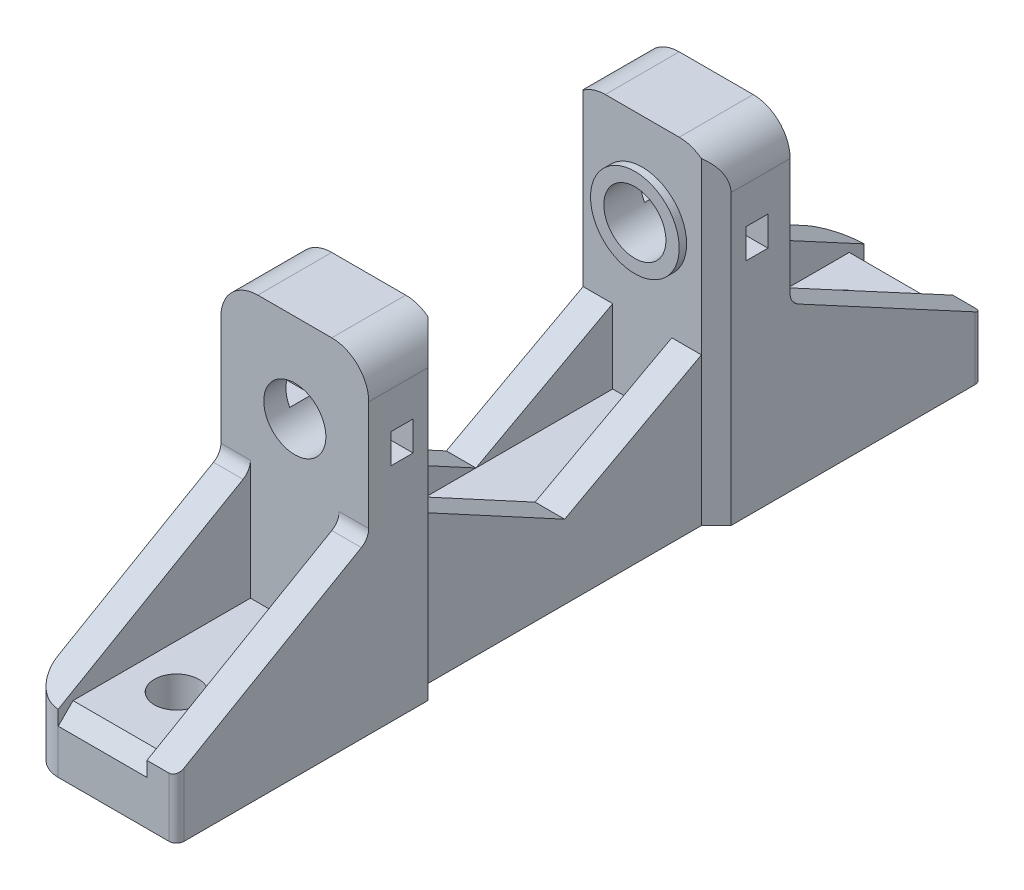
SolidWorks part; units mm, degrees
ref_plane "Спереди" through (0, 0, 0) normal (0, 0, 1) x (1, 0, 0)
ref_plane "Сверху" through (0, 0, 0) normal (0, 1, 0) x (1, 0, 0)
ref_plane "Справа" through (0, 0, 0) normal (1, 0, 0) x (0, 0, -1)
sketch "Эскиз1" plane through (0, 0, 0) normal (0, 0, 1) x (1, 0, 0)
  line L0 (-10, 0) -> (10, 0)
  line L2 (-10, 0) -> (-10, 44)
  line L3 (-10, 44) -> (10, 44)
  line L4 (10, 44) -> (10, 0)
  circle A0 centre (0, 32) radius 4.2
extrude "Бобышка-Вытянуть1" add sketch "Эскиз1" along normal blind 7
ref_plane "Плоскость1" through (0, 0, 7) normal (0, 0, 1) x (1, 0, 0)
sketch "Эскиз2" plane through (0, 0, 7) normal (0, 0, 1) x (1, 0, 0)
  line L0 (-10, 44) -> (10, 44)
  line L1 (10, 44) -> (10, 0)
  line L2 (10, 0) -> (-10, 0)
  line L3 (-10, 0) -> (-10, 44)
extrude "Бобышка-Вытянуть2" add sketch "Эскиз2" along normal blind 3
sketch "Эскиз3" plane through (0, 0, 0) normal (0, 1, 0) x (1, 0, 0)
  line L0 (-10, -10) -> (-10, -36)
  line L1 (-10, -36) -> (10, -36)
  line L2 (10, -36) -> (10, -10)
  line L3 (-10, -10) -> (10, -10)
  circle A0 centre (0, -26) radius 3
extrude "Бобышка-Вытянуть4" add sketch "Эскиз3" along normal blind 8
ref_plane "Плоскость2" through (-10, 0, 0) normal (-1, 0, 0) x (0, 0, 1)
sketch "Эскиз4" plane through (-10, 0, 0) normal (-1, 0, 0) x (0, 0, 1)
  line L0 (36, 8) -> (10, 8)
  line L1 (10, 8) -> (10, 23)
  line L2 (10, 44) -> (10, 8) construction
  line L3 (10, 23) -> (36, 8)
extrude "Бобышка-Вытянуть5" add sketch "Эскиз4" against normal blind 4
ref_plane "Плоскость3" through (10, 0, 0) normal (1, 0, 0) x (0, 0, -1)
sketch "Эскиз5" plane through (10, 0, 0) normal (1, 0, 0) x (0, 0, -1)
  line L0 (-36, 8) -> (-10, 23)
  line L1 (-10, 8) -> (-10, 44) construction
  line L2 (-36, 8) -> (-10, 23) construction
  line L3 (-10, 23) -> (-10, 8)
  line L4 (-10, 8) -> (-36, 8)
extrude "Бобышка-Вытянуть6" add sketch "Эскиз5" against normal blind 4
chamfer "Фаска1" distance 2 angle 45 2 edges at (10, 22, 0) (-10, 22, 0)
fillet "Скругление2" radius 5 2 edges at (-10, 44, 6) (10, 44, 6)
fillet "Скругление3" radius 1 1 edges at (10, 4, 36)
fillet "Скругление4" radius 2 2 edges at (8, 23, 10) (-8, 23, 10)
sketch "Эскиз6" plane through (0, 0, 0) normal (0, 1, 0) x (1, 0, 0)
  line L2 (8, 37) -> (-8, 37)
  line L3 (-8, 37) -> (-8, 0)
  line L4 (8, 37) -> (8, 0)
  line L5 (5, 0) -> (-5, 0) construction
  line L6 (8, 0) -> (-8, 0)
extrude "Бобышка-Вытянуть7" add sketch "Эскиз6" along normal blind 10
ref_plane "Плоскость4" through (0, 0, -37) normal (0, 0, -1) x (-1, 0, 0)
sketch "Эскиз7" plane through (0, 0, -37) normal (0, 0, -1) x (-1, 0, 0)
  line L0 (0, 0) -> (-10, 0)
  line L1 (-10, 21.45) -> (-10, -21.45) construction
  line L2 (-8, 0) -> (-10, 0) construction
  line L3 (-10, 0) -> (-10, 44)
  line L4 (-10, 44) -> (10, 44)
  line L5 (10, 44) -> (10, 0)
  line L6 (10, -21.45) -> (10, 21.45) construction
  line L7 (10, 0) -> (0, 0)
  circle A0 centre (0, 32) radius 4.2
extrude "Бобышка-Вытянуть8" add sketch "Эскиз7" along normal blind 7
chamfer "Фаска2" distance 2 angle 45 2 edges at (10, 22, -37) (-10, 22, -37)
ref_plane "Плоскость5" through (0, 0, -44) normal (0, 0, -1) x (-1, 0, 0)
sketch "Эскиз8" plane through (0, 0, -44) normal (0, 0, -1) x (-1, 0, 0)
  line L0 (-10, 0) -> (10, 0)
  line L1 (-10, 0) -> (10, 0) construction
  line L2 (-10, 21.45) -> (-10, -21.45) construction
  line L3 (10, 0) -> (10, 44)
  line L4 (10, 44) -> (-10, 44)
  line L5 (-10, 44) -> (-10, 0)
extrude "Бобышка-Вытянуть9" add sketch "Эскиз8" along normal blind 3
sketch "Эскиз9" plane through (0, 0, 0) normal (0, 1, 0) x (1, 0, 0)
  line L0 (-10, 47) -> (-10, 73)
  line L1 (-10, 73) -> (10, 73)
  line L2 (10, 73) -> (10, 47)
  line L3 (10, 47) -> (-10, 47)
  circle A0 centre (0, 64) radius 3
extrude "Бобышка-Вытянуть10" add sketch "Эскиз9" along normal blind 8
sketch "Эскиз10" plane through (-10, 0, 0) normal (-1, 0, 0) x (0, 0, 1)
  line L0 (-73, 8) -> (-47, 8)
  line L1 (-47, 8) -> (-47, 22)
  line L2 (-47, 8) -> (-47, 44) construction
  line L3 (-47, 22) -> (-73, 8)
extrude "Бобышка-Вытянуть11" add sketch "Эскиз10" against normal blind 4
sketch "Эскиз11" plane through (10, 0, 0) normal (1, 0, 0) x (0, 0, -1)
  line L0 (47, 8) -> (47, 22)
  line L1 (47, 22) -> (73, 8)
  line L2 (73, 8) -> (47, 8)
extrude "Бобышка-Вытянуть12" add sketch "Эскиз11" against normal blind 4
fillet "Скругление5" radius 2 2 edges at (8, 22, -47) (-8, 22, -47)
fillet "Скругление7" radius 1 1 edges at (10, 4, -73)
fillet "Скругление8" radius 5 2 edges at (-10, 44, -43) (10, 44, -43)
sketch "Эскиз12" plane through (10, 0, 0) normal (1, 0, 0) x (0, 0, -1)
  line L0 (-7, 30) -> (-7, 34)
  line L3 (-7, 55) -> (-7, -55) construction
  line L5 (-7, 34) -> (-4, 34)
  line L6 (-4, 34) -> (-4, 30)
  line L7 (-4, 30) -> (-7, 30)
  line L9 (41, 30) -> (41, 34)
  line L10 (41, 34) -> (44, 34)
  line L11 (44, -55) -> (44, 55) construction
  line L12 (44, 34) -> (44, 30)
  line L13 (44, 30) -> (41, 30)
extrude "Вырез-Вытянуть1" cut sketch "Эскиз12" against normal through all
ref_plane "Плоскость6" through (8, 0, 0) normal (1, 0, 0) x (0, 0, -1)
sketch "Эскиз13" plane through (8, 0, 0) normal (1, 0, 0) x (0, 0, -1)
  line L0 (0, 10) -> (0, 20)
  line L1 (0, 43) -> (0, 10) construction
  line L2 (0, 10) -> (18.5, 10)
  line L3 (0, 10) -> (37, 10) construction
  line L4 (18.5, 10) -> (0, 20)
  line L5 (18.5, 10) -> (37, 10)
  line L6 (37, -25.6899) -> (37, 25.6899) construction
  line L7 (37, 10) -> (37, 20)
  line L8 (37, 20) -> (18.5, 10)
extrude "Бобышка-Вытянуть13" add sketch "Эскиз13" against normal blind 4 contours L2 L4 L0 | L7 L8 L5
ref_plane "Плоскость7" through (-8, 0, 0) normal (-1, 0, 0) x (0, 0, 1)
sketch "Эскиз14" plane through (-8, 0, 0) normal (-1, 0, 0) x (0, 0, 1)
  line L0 (-37, 10) -> (-37, 20)
  line L1 (-37, 25.6899) -> (-37, -25.6899) construction
  line L2 (-37, 20) -> (-18.5, 10)
  line L3 (-37, 10) -> (0, 10) construction
  line L4 (-18.5, 10) -> (0, 20)
  line L5 (0, 10) -> (0, 43) construction
  line L6 (-18.5, 10) -> (0, 20) construction
  line L7 (0, 20) -> (0, 10)
  line L8 (-37, 10) -> (-18.5, 10)
  line L9 (0, 10) -> (-18.5, 10)
extrude "Бобышка-Вытянуть14" add sketch "Эскиз14" against normal blind 4 contours L9 L7 L4 | L0 L8 L2
sketch "Эскиз15" plane through (0, 0, -37) normal (0, 0, -1) x (-1, 0, 0)
  circle A0 centre (0, 32) radius 4.2
extrude "Вырез-Вытянуть2" cut sketch "Эскиз15" against normal through all both and the other way through all
sketch "Эскиз16" plane through (0, 0, -37) normal (0, 0, -1) x (-1, 0, 0)
  circle A0 centre (0, 32) radius 4.2
  circle A1 centre (0, 32) radius 6
extrude "Бобышка-Вытянуть15" add sketch "Эскиз16" against normal blind 1
ref_plane "Плоскость12" through (0, 0, 0) normal (0, 0, -1) x (-1, 0, 0)
sketch "Эскиз17" plane through (0, 0, 0) normal (0, 0, -1) x (-1, 0, 0)
  circle A0 centre (0, 32) radius 4.2
  circle A1 centre (0, 32) radius 6
extrude "Бобышка-Вытянуть16" add sketch "Эскиз17" along normal blind 1
chamfer "Фаска3" distance 2 angle 45 2 edges at (0, 8, 36) (0, 8, -73)
fillet "Скругление9" radius 4 2 edges at (-10, 4, 36) (-10, 4, -73)
